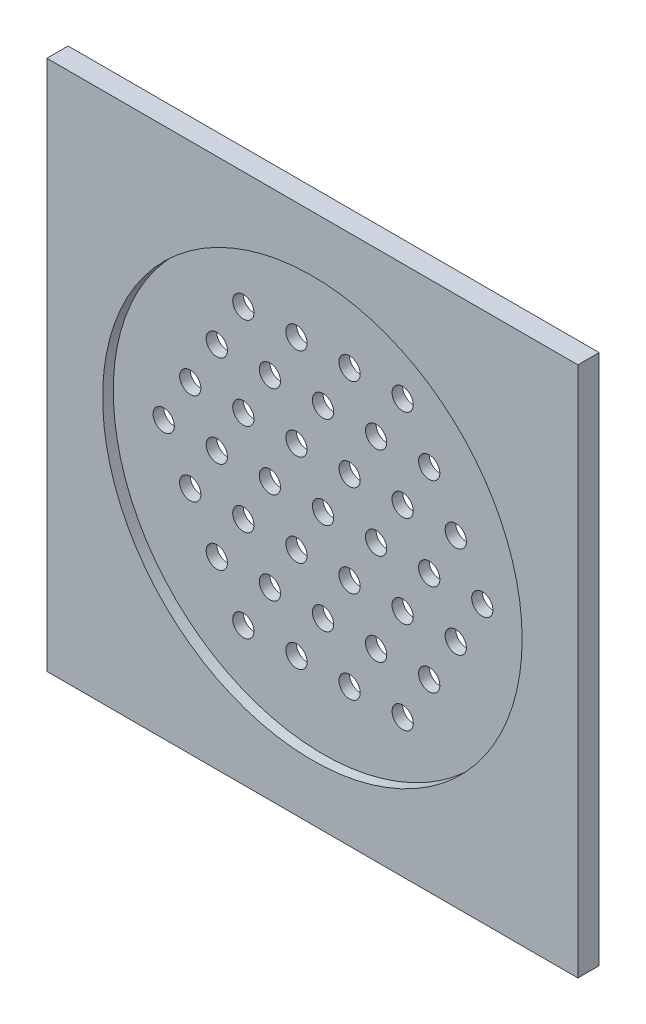
SolidWorks part; units mm, degrees
material "Сосна"
ref_plane "Front" through (0, 0, 0) normal (0, 0, 1) x (1, 0, 0)
ref_plane "Top" through (0, 0, 0) normal (0, 1, 0) x (1, 0, 0)
ref_plane "Right" through (0, 0, 0) normal (1, 0, 0) x (0, 0, -1)
sketch "Эскиз1" plane through (0, 66.7543, 0) normal (0, 0, 1) x (-1, 0, 0)
  line L36 (0, 66.7543) -> (50, 66.7543)
  line L37 (0, 66.7543) -> (0, 16.7543)
  line L38 (0, 16.7543) -> (50, 16.7543)
  line L39 (50, 66.7543) -> (50, 16.7543)
  point P5 (0, 0)
  dimension "D1" = 50
  dimension "D2" = 50
extrude "Бобышка-Вытянуть1" add sketch "Эскиз1" along normal blind 2
sketch "Эскиз2" plane through (0, 0, 2) normal (0, 0, 1) x (1, 0, 0)
  line L0 (-20, 16.3397) -> (-30, 16.3397) construction
  line L1 (-32.5, 12.0096) -> (-27.5, 12.0096) construction
  line L2 (-27.5, 12.0096) -> (-22.5, 12.0096) construction
  line L4 (-17.5, 12.0096) -> (-22.5, 12.0096) construction
  circle A1 centre (-25, 25) radius 1
  circle A2 centre (-20, 25) radius 1
  circle A3 centre (-15, 25) radius 1
  circle A4 centre (-10, 25) radius 1
  circle A5 centre (-22.5, 20.6699) radius 1
  circle A6 centre (-20, 16.3397) radius 1
  circle A7 centre (-17.5, 12.0096) radius 1
  circle A8 centre (-27.5, 20.6699) radius 1
  circle A9 centre (-30, 16.3397) radius 1
  circle A10 centre (-32.5, 12.0096) radius 1
  circle A11 centre (-30, 25) radius 1
  circle A12 centre (-35, 25) radius 1
  circle A13 centre (-40, 25) radius 1
  circle A14 centre (-27.5, 29.3301) radius 1
  circle A15 centre (-30, 33.6603) radius 1
  circle A16 centre (-32.5, 37.9904) radius 1
  circle A17 centre (-22.5, 29.3301) radius 1
  circle A18 centre (-20, 33.6603) radius 1
  circle A19 centre (-17.5, 37.9904) radius 1
  circle A20 centre (-25, 16.3397) radius 1
  circle A21 centre (-27.5, 12.0096) radius 1
  circle A22 centre (-22.5, 12.0096) radius 1
  circle A23 centre (-32.5, 20.6699) radius 1
  circle A24 centre (-37.5, 20.6699) radius 1
  circle A25 centre (-35, 16.3397) radius 1
  circle A26 centre (-32.5, 29.3301) radius 1
  circle A27 centre (-35, 33.6603) radius 1
  circle A28 centre (-37.5, 29.3301) radius 1
  circle A29 centre (-25, 33.6603) radius 1
  circle A30 centre (-22.5, 37.9904) radius 1
  circle A31 centre (-27.5, 37.9904) radius 1
  circle A32 centre (-17.5, 29.3301) radius 1
  circle A33 centre (-12.5, 29.3301) radius 1
  circle A34 centre (-15, 33.6603) radius 1
  circle A35 centre (-17.5, 20.6699) radius 1
  circle A36 centre (-15, 16.3397) radius 1
  circle A37 centre (-12.5, 20.6699) radius 1
  point P1 (0, 0)
  point P4 (-11.3489, 21.2095)
  point P42 (-25, 25)
  point P46 (-24.8485, 26.1035)
  point P80 (-25, 25)
  point P92 (-25, 16.3397)
  dimension "D1" = 4
  dimension "D6" = 2
  dimension "D3" = 3
  dimension "D7" = 25
  dimension "D8" = 25
  dimension "D9" = 10
  dimension "D4" = 2
  dimension "D2" = 6
  dimension "D5" = 6
extrude "Отверстия для динамика" cut sketch "Эскиз2" against normal through all
sketch "Эскиз3" plane through (0, 0, 2) normal (0, 0, 1) x (1, 0, 0)
  circle A0 centre (-25, 25) radius 19.75
  dimension "D1" = 39.5
extrude "Вырез под динамик" cut sketch "Эскиз3" against normal blind 1
